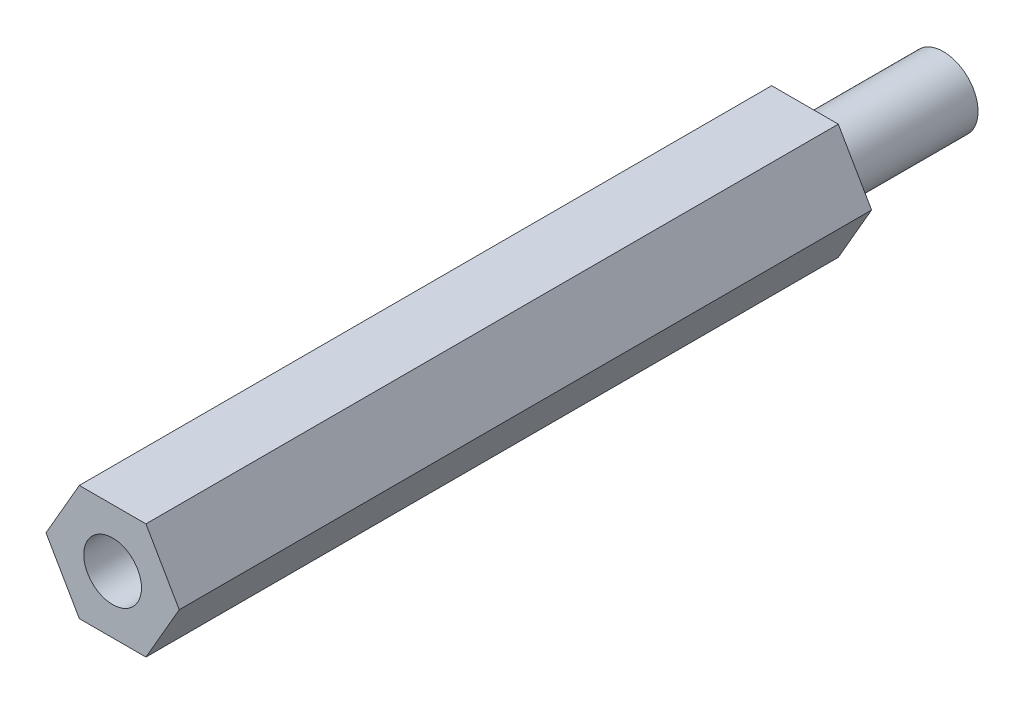
SolidWorks part; units mm, degrees
material "黃銅"
ref_plane "前基準面" through (0, 0, 0) normal (0, 0, 1) x (1, 0, 0)
ref_plane "上基準面" through (0, 0, 0) normal (0, 1, 0) x (1, 0, 0)
ref_plane "右基準面" through (0, 0, 0) normal (1, 0, 0) x (0, 0, -1)
sketch "草圖1" plane through (0, 0, 0) normal (0, 0, 1) x (1, 0, 0)
  line L1 (-1.4434, 2.5) -> (-2.8868, 0)
  line L2 (-2.8868, 0) -> (-1.4434, -2.5)
  line L3 (-1.4434, -2.5) -> (1.4434, -2.5)
  line L4 (1.4434, -2.5) -> (2.8868, 0)
  line L5 (2.8868, 0) -> (1.4434, 2.5)
  line L6 (1.4434, 2.5) -> (-1.4434, 2.5)
  circle A0 centre (0, 0) radius 2.5 construction
  dimension "D1" = 5
extrude "填料-伸長1" add sketch "草圖1" along normal blind 30
sketch "草圖4" plane through (0, 0, 0) normal (0, 0, -1) x (-1, 0, 0)
  circle A0 centre (0, 0) radius 1.5
  dimension "D1" = 3
extrude "填料-伸長2" add sketch "草圖4" along normal blind 6
hole_wizard "M3x0.5 螺紋孔1" positions "草圖2" profile "草圖3" tap size "M3x0.5" standard "Ansi Metric"
sketch "草圖2" plane through (0, 0, 30) normal (0, 0, 1) x (1, 0, 0)
  point P0 (0, 0)
sketch "草圖3" plane through (0, 0, 30) normal (1, 0, 0) x (0, -1, 0)
  line L0 (0, 0) -> (0, 8.2511)
  line L1 (0, 8.2511) -> (1.25, 7.5)
  line L2 (1.25, 7.5) -> (1.25, 0)
  line L5 (1.25, 0) -> (0, 0)
  line L10 (0, 8.2511) -> (-1.25, 7.5) construction
  line L11 (0, -6.35) -> (0, 107.95) construction
  dimension "螺孔鑽直徑" = 2.5
  dimension "螺孔鑽深度" = 7.5
  dimension "導頭角度" = 118
